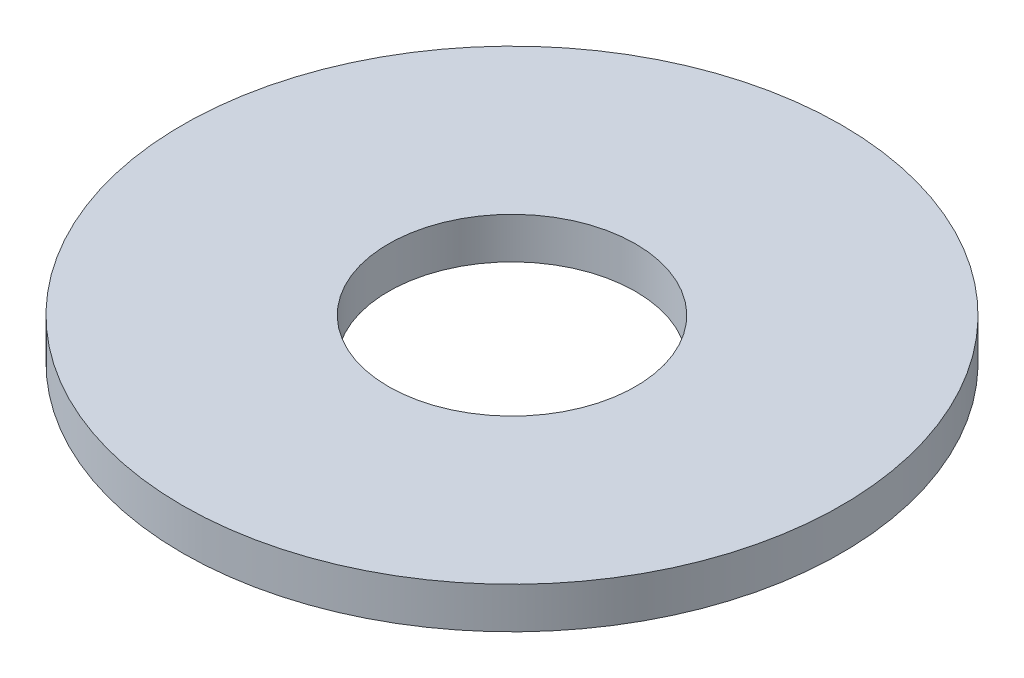
SolidWorks part; units mm, degrees
material "黄铜"
ref_plane "前视基准面" through (0, 0, 0) normal (0, 0, 1) x (1, 0, 0)
ref_plane "上视基准面" through (0, 0, 0) normal (0, 1, 0) x (1, 0, 0)
ref_plane "右视基准面" through (0, 0, 0) normal (1, 0, 0) x (0, 0, -1)
sketch "草图1" plane through (0, 0, 0) normal (0, 1, 0) x (1, 0, 0)
  circle A0 centre (0, 0) radius 1.5
  circle A1 centre (0, 0) radius 4
  dimension "D1" = 3
  dimension "D2" = 8
extrude "凸台-拉伸1" add sketch "草图1" along normal blind 0.5
